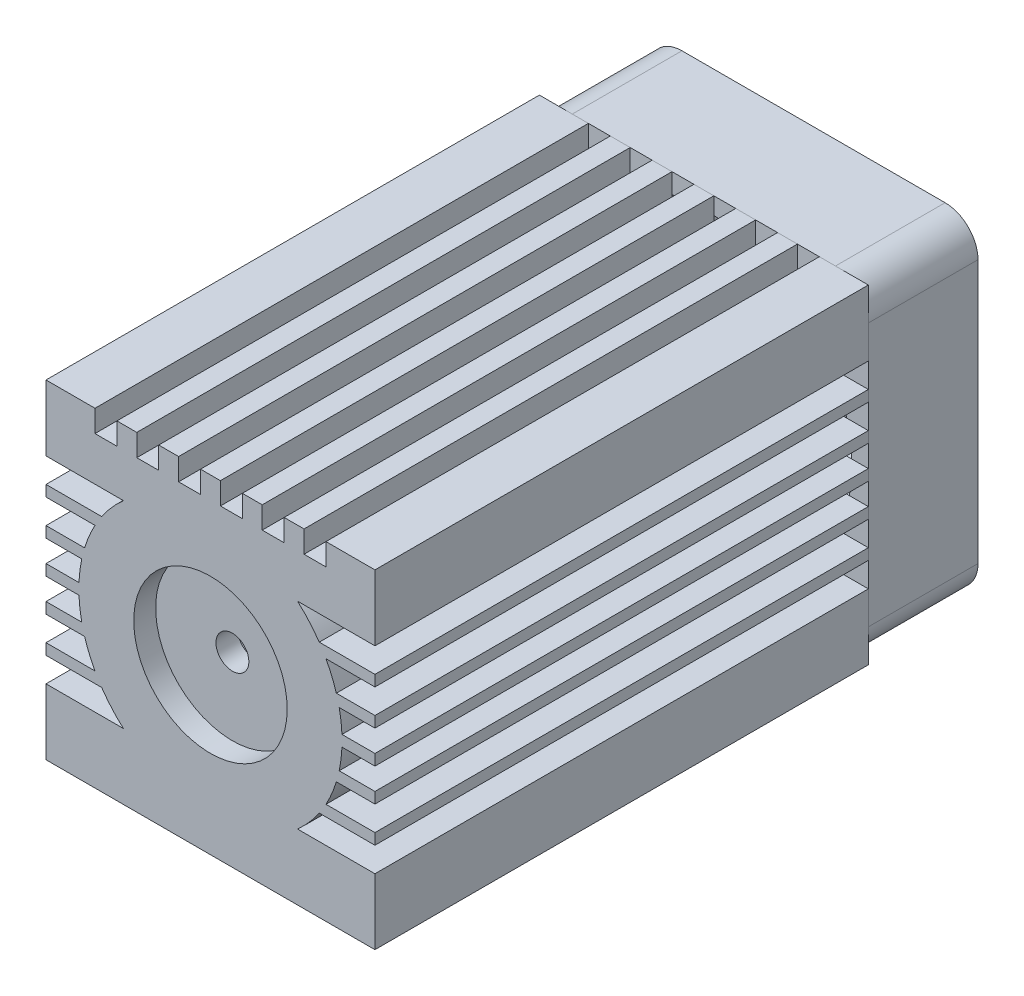
SolidWorks part; units mm, degrees
ref_plane "Front Plane" through (0, 0, 0) normal (0, 0, 1) x (1, 0, 0)
ref_plane "Top Plane" through (0, 0, 0) normal (0, 1, 0) x (1, 0, 0)
ref_plane "Right Plane" through (0, 0, 0) normal (1, 0, 0) x (0, 0, -1)
sketch "Sketch1" plane through (0, 0, 0) normal (0, 0, 1) x (1, 0, 0)
  line L0 (-15, -9) -> (-7.9373, -9)
  line L1 (-15, -15) -> (15, -15)
  line L2 (-15, -15) -> (-15, -9)
  line L3 (-15, 15) -> (-10.5327, 15)
  line L4 (15, -15) -> (15, -9)
  line L5 (-15, -15) -> (15, 15) construction
  line L6 (-15, 15) -> (15, -15) construction
  line L11 (15, -6.75) -> (9.9216, -6.75)
  line L12 (-15, -5.75) -> (-10.5327, -5.75)
  line L13 (-15, -3.5) -> (-11.4782, -3.5)
  line L14 (-15, -2.5) -> (-11.7367, -2.5)
  line L15 (-15, -0.5) -> (-11.9896, -0.5)
  line L16 (55, 0) -> (-55, 0) construction
  line L17 (-15, 0.5) -> (-11.9896, 0.5)
  line L18 (-15, 2.5) -> (-11.7367, 2.5)
  line L19 (-15, 3.5) -> (-11.4782, 3.5)
  line L20 (-15, 5.75) -> (-10.5327, 5.75)
  line L21 (15, 6.75) -> (9.9216, 6.75)
  line L22 (-15, 9) -> (-7.9373, 9)
  line L23 (7.9373, 9) -> (15, 9)
  line L24 (-9.9216, 6.75) -> (-15, 6.75)
  line L25 (10.5327, 5.75) -> (15, 5.75)
  line L26 (11.4782, 3.5) -> (15, 3.5)
  line L27 (11.7367, 2.5) -> (15, 2.5)
  line L28 (11.9896, 0.5) -> (15, 0.5)
  line L29 (7.9373, -9) -> (15, -9)
  line L30 (-9.9216, -6.75) -> (-15, -6.75)
  line L31 (10.5327, -5.75) -> (15, -5.75)
  line L32 (11.4782, -3.5) -> (15, -3.5)
  line L33 (11.7367, -2.5) -> (15, -2.5)
  line L34 (11.9896, -0.5) -> (15, -0.5)
  line L35 (-15, 9) -> (-15, 15)
  line L36 (-15, 5.75) -> (-15, 6.75)
  line L37 (-15, 2.5) -> (-15, 3.5)
  line L38 (-15, -0.5) -> (-15, 0.5)
  line L39 (-15, -3.5) -> (-15, -2.5)
  line L40 (-15, -6.75) -> (-15, -5.75)
  line L41 (15, 9) -> (15, 15)
  line L42 (15, 5.75) -> (15, 6.75)
  line L43 (15, 2.5) -> (15, 3.5)
  line L44 (15, -0.5) -> (15, 0.5)
  line L45 (15, -3.5) -> (15, -2.5)
  line L46 (15, -6.75) -> (15, -5.75)
  line L47 (-10.5327, 15) -> (-10.5327, 13)
  line L48 (-10.5327, 13) -> (-8.5327, 13)
  line L49 (-8.5327, 13) -> (-8.5327, 15)
  line L50 (-6.7196, 15) -> (-6.7196, 13)
  line L51 (-6.7196, 13) -> (-4.7196, 13)
  line L52 (-4.7196, 13) -> (-4.7196, 15)
  line L53 (-2.9065, 15) -> (-2.9065, 13)
  line L54 (-2.9065, 13) -> (-0.9065, 13)
  line L55 (-0.9065, 13) -> (-0.9065, 15)
  line L56 (0.9065, 15) -> (0.9065, 13)
  line L57 (0.9065, 13) -> (2.9065, 13)
  line L58 (2.9065, 13) -> (2.9065, 15)
  line L59 (4.7196, 15) -> (4.7196, 13)
  line L60 (4.7196, 13) -> (6.7196, 13)
  line L61 (6.7196, 13) -> (6.7196, 15)
  line L62 (8.5327, 15) -> (8.5327, 13)
  line L63 (8.5327, 13) -> (10.5327, 13)
  line L64 (10.5327, 13) -> (10.5327, 15)
  line L65 (-0.9065, 13) -> (0.9065, 13) construction
  line L66 (-8.5327, 15) -> (-6.7196, 15)
  line L67 (-4.7196, 15) -> (-2.9065, 15)
  line L68 (-0.9065, 15) -> (0.9065, 15)
  line L69 (2.9065, 15) -> (4.7196, 15)
  line L70 (6.7196, 15) -> (8.5327, 15)
  line L71 (10.5327, 15) -> (15, 15)
  arc A0 (-9.9216, -6.75) -> (-7.9373, -9) centre (0, 0) ccw
  arc A1 (-11.4782, -3.5) -> (-10.5327, -5.75) centre (0, 0) ccw
  arc A2 (-11.9896, -0.5) -> (-11.7367, -2.5) centre (0, 0) ccw
  arc A3 (-11.7367, 2.5) -> (-11.9896, 0.5) centre (0, 0) ccw
  arc A4 (-10.5327, 5.75) -> (-11.4782, 3.5) centre (0, 0) ccw
  arc A5 (-7.9373, 9) -> (-9.9216, 6.75) centre (0, 0) ccw
  arc A6 (7.9373, -9) -> (9.9216, -6.75) centre (0, 0) ccw
  arc A7 (10.5327, -5.75) -> (11.4782, -3.5) centre (0, 0) ccw
  arc A8 (11.7367, -2.5) -> (11.9896, -0.5) centre (0, 0) ccw
  arc A9 (11.9896, 0.5) -> (11.7367, 2.5) centre (0, 0) ccw
  arc A10 (11.4782, 3.5) -> (10.5327, 5.75) centre (0, 0) ccw
  arc A11 (9.9216, 6.75) -> (7.9373, 9) centre (0, 0) ccw
  point P0 (0, 0)
  point P60 (0, 13)
  point P62 (-8.5327, 13)
  point P83 (-36.4156, 19.802)
  dimension "D3" = 24
  dimension "D1" = 30
  dimension "D2" = 30
  dimension "D4" = 6
  dimension "D5" = 2.25
  dimension "D6" = 1
  dimension "D7" = 2.25
  dimension "D8" = 1
  dimension "D9" = 0.5
  dimension "D10" = 2
  dimension "D11" = 2
  dimension "D12" = 6
extrude "Boss-Extrude1" add sketch "Sketch1" against normal blind 45
sketch "Sketch2" plane through (0, 0, 0) normal (0, 0, 1) x (1, 0, 0)
  circle A0 centre (0, 0) radius 7
  dimension "D1" = 14
extrude "Cut-Extrude1" cut sketch "Sketch2" against normal blind 2
sketch "Sketch3" plane through (0, 0, -2) normal (0, 0, 1) x (1, 0, 0)
  circle A0 centre (0, 0) radius 1.5
  dimension "D1" = 3
extrude "Cut-Extrude2" cut sketch "Sketch3" against normal blind 2
sketch "Sketch4" plane through (0, -15, 0) normal (0, -1, 0) x (1, 0, 0)
  line L0 (-15, 0) -> (15, 0) construction
  line L1 (-15, -22.5) -> (15, -22.5) construction
  line L2 (-15, -45) -> (-15, 0) construction
  line L3 (15, -45) -> (15, 0) construction
  circle A0 centre (-8, -2.25) radius 1.25
  circle A1 centre (0, -2.25) radius 1.25
  circle A2 centre (8, -2.25) radius 1.25
  circle A3 centre (8, -42.75) radius 1.25
  circle A4 centre (0, -42.75) radius 1.25
  circle A5 centre (-8, -42.75) radius 1.25
  dimension "D4" = 2.5
  dimension "D1" = 8
  dimension "D2" = 8
  dimension "D3" = 2.25
extrude "Cut-Extrude5" cut sketch "Sketch4" against normal blind 4
sketch "Sketch5" plane through (0, 0, -45) normal (0, 0, -1) x (-1, 0, 0)
  line L1 (-12, 15) -> (12, 15)
  line L2 (-15, 12) -> (-15, -12)
  line L3 (-12, -15) -> (12, -15)
  line L4 (15, 12) -> (15, -12)
  circle A0 centre (0, 0) radius 13.5
  arc A1 (-15, -12) -> (-12, -15) centre (-12, -12) ccw
  arc A2 (12, -15) -> (15, -12) centre (12, -12) ccw
  arc A3 (12, 15) -> (15, 12) centre (12, 12) cw
  arc A4 (-12, 15) -> (-15, 12) centre (-12, 12) ccw
  point P13 (15, -15)
  point P18 (-15, 15)
  dimension "D1" = 27
  dimension "D2" = 3
extrude "Boss-Extrude2" add sketch "Sketch5" along normal blind 10 separate body
sketch "Sketch6" plane through (0, 0, -45) normal (0, 0, -1) x (-1, 0, 0)
  circle A0 centre (0, 0) radius 8.5
  dimension "D1" = 17
extrude "Boss-Extrude3" add sketch "Sketch6" along normal blind 10 separate body
ref_plane "Plane1" through (0, 0, 0) normal (0, -1, 0) x (-1, 0, 0)
sketch "Sketch7" plane through (0, 0, 0) normal (0, -1, 0) x (-1, 0, 0)
  line L0 (-4, 53.2929) -> (-3.2929, 54)
  line L1 (-3.2929, 54) -> (4, 46.7071)
  line L2 (4, 46.7071) -> (3.2929, 46)
  line L3 (3.2929, 46) -> (-4, 53.2929)
  line L4 (-12, 55) -> (12, 55) construction
  line L5 (0.3536, 50.3536) -> (-0.3536, 49.6464) construction
  point P8 (0, 50)
  point P9 (3.2039, 46)
  dimension "D1" = 8
  dimension "D2" = 1
  dimension "D3" = 1
  dimension "D4" = 45
extrude "Boss-Extrude4" add sketch "Sketch7" along normal blind 12
pattern_circular "CirPattern1" count 5 over 360 about axis through (0, 0, 0) along (0, 0, 1) of "Boss-Extrude4"
